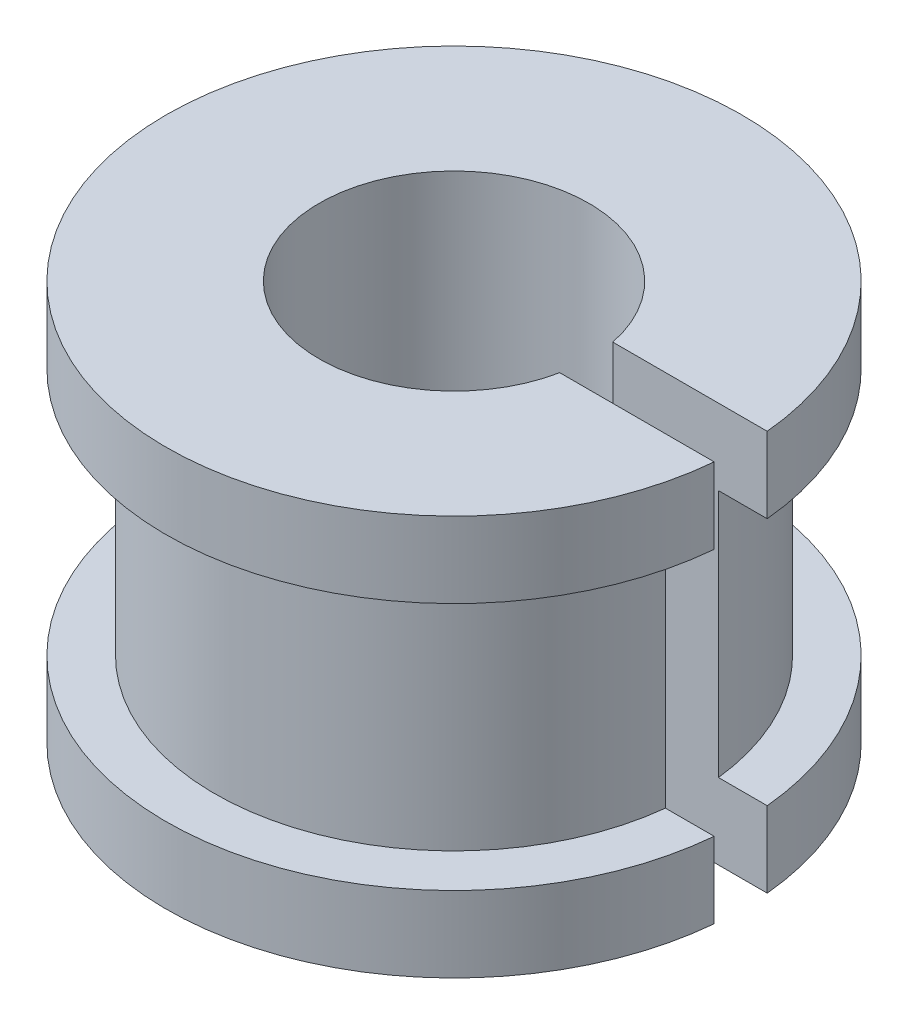
SolidWorks part; units mm, degrees
ref_plane "Front Plane" through (0, 0, 0) normal (0, 0, 1) x (1, 0, 0)
ref_plane "Top Plane" through (0, 0, 0) normal (0, 1, 0) x (1, 0, 0)
ref_plane "Right Plane" through (0, 0, 0) normal (1, 0, 0) x (0, 0, -1)
sketch "Sketch1" plane through (0, 0, 0) normal (0, 1, 0) x (1, 0, 0)
  circle A0 centre (0, 0) radius 9.5
  dimension "D1" = 19
extrude "Boss-Extrude1" add sketch "Sketch1" along normal blind 2.5
sketch "Sketch2" plane through (0, 2.5, 0) normal (0, 1, 0) x (1, 0, 0)
  circle A0 centre (0, 0) radius 7.9
  dimension "D1" = 15.8
extrude "Boss-Extrude2" add sketch "Sketch2" along normal blind 8.2
sketch "Sketch3" plane through (0, 10.7, 0) normal (0, 1, 0) x (1, 0, 0)
  circle A0 centre (0, 0) radius 9.5
  dimension "D1" = 19
extrude "Boss-Extrude3" add sketch "Sketch3" along normal blind 2.5
sketch "Sketch4" plane through (0, 13.2, 0) normal (0, 1, 0) x (1, 0, 0)
  line L0 (0, 0) -> (0.8064, 0) construction
  line L5 (0.8064, 0.875) -> (0.8064, -0.875)
  line L6 (0.8064, -0.875) -> (10.9974, -0.875)
  line L7 (0.8064, 0.875) -> (10.9974, 0.875)
  line L8 (10.9974, 0.875) -> (10.9974, -0.875)
  circle A0 centre (0, 0) radius 4.45
  point P5 (0.8064, 0)
  dimension "D1" = 8.9
  dimension "D2" = 1.75
extrude "Cut-Extrude1" cut sketch "Sketch4" against normal through all
